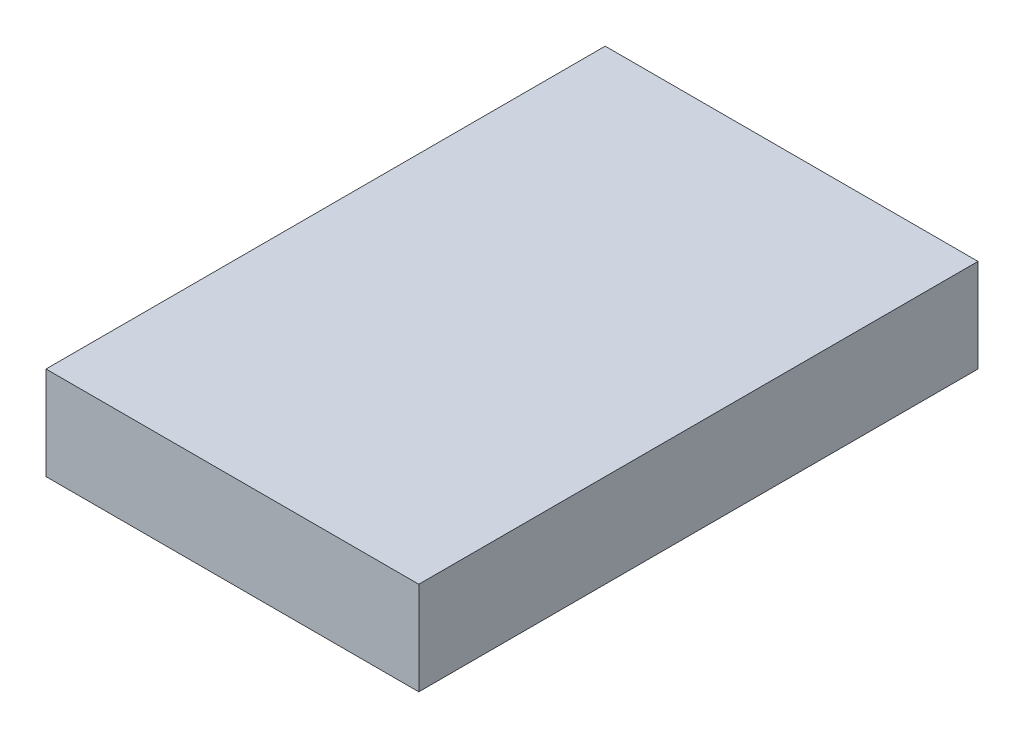
SolidWorks part; units mm, degrees
ref_plane "Front Plane" through (0, 0, 0) normal (0, 0, 1) x (1, 0, 0)
ref_plane "Top Plane" through (0, 0, 0) normal (0, 1, 0) x (1, 0, 0)
ref_plane "Right Plane" through (0, 0, 0) normal (1, 0, 0) x (0, 0, -1)
sketch "Sketch1" plane through (0, 0, 0) normal (0, 0, 1) x (1, 0, 0)
  line L1 (-20, 5) -> (20, 5)
  line L2 (-20, 5) -> (-20, -5)
  line L3 (-20, -5) -> (20, -5)
  line L4 (20, 5) -> (20, -5)
  line L5 (-20, 5) -> (20, -5) construction
  line L6 (-20, -5) -> (20, 5) construction
  point P0 (0, 0)
  dimension "D1" = 10
  dimension "D2" = 40
extrude "Boss-Extrude1" add sketch "Sketch1" along normal blind 60
ref_plane "Plane1" through (0, 0, 0) normal (0, 1, 0) x (1, 0, 0)
sketch "Sketch2" plane through (0, 0, 0) normal (0, 1, 0) x (1, 0, 0)
  line L1 (-20, -60) -> (20, -60) construction
  line L5 (0, -50) -> (0, -46)
  line L6 (1, -45) -> (15, -45)
  line L7 (15, -42) -> (0, -42)
  line L8 (0, -42) -> (-15, -42)
  line L9 (-15, -39) -> (15, -39)
  line L10 (15, -36) -> (-15, -36)
  line L11 (-15, -33) -> (15.3556, -33)
  line L12 (15.3556, -30) -> (-15, -30)
  line L13 (-15, -27) -> (15, -27)
  line L14 (15, -24) -> (-15, -24)
  line L15 (-15, -21) -> (15, -21)
  line L16 (15, -18) -> (-15, -18)
  line L17 (-15, -15) -> (15, -15)
  line L18 (15, -12) -> (1, -12)
  line L19 (0, -11) -> (0, -6)
  arc A0 (15, -45) -> (15, -42) centre (15, -43.5) ccw
  arc A1 (-15, -42) -> (-15, -39) centre (-15, -40.5) cw
  arc A2 (15, -39) -> (15, -36) centre (15, -37.5) ccw
  arc A3 (-15, -36) -> (-15, -33) centre (-15, -34.5) cw
  arc A4 (15.3556, -33) -> (15.3556, -30) centre (15.3556, -31.5) ccw
  arc A5 (-15, -30) -> (-15, -27) centre (-15, -28.5) cw
  arc A6 (15, -27) -> (15, -24) centre (15, -25.5) ccw
  arc A7 (-15, -24) -> (-15, -21) centre (-15, -22.5) cw
  arc A8 (15, -21) -> (15, -18) centre (15, -19.5) ccw
  arc A9 (-15, -18) -> (-15, -15) centre (-15, -16.5) cw
  arc A10 (15, -15) -> (15, -12) centre (15, -13.5) ccw
  arc A11 (0, -46) -> (1, -45) centre (1, -46) cw
  arc A12 (1, -12) -> (0, -11) centre (1, -11) cw
  point P5 (0, -45)
  point P9 (0, -12)
  dimension "D5" = 1
  dimension "D1" = 10
  dimension "D2" = 5
  dimension "D3" = 15
  dimension "D4" = 15
  dimension "D16" = 6
ref_plane "Plane2" through (0, 0, 6) normal (0, 0, -1) x (-1, 0, 0)
sketch "Sketch10" plane through (0, 0, 6) normal (0, 0, -1) x (-1, 0, 0)
  circle A0 centre (0, 0) radius 0.5
  dimension "D1" = 1
sketch "Sketch11" plane through (0, 0, 6) normal (0, 0, -1) x (-1, 0, 0)
sweep "Cut-Sweep1" cut profiles "Sketch10" path "Sketch2"
ref_plane "Plane4" through (0, 0, 0) normal (1, 0, 0) x (0, 0, -1)
ref_plane "Plane5" through (0, 0, 0) normal (0, 1, 0) x (1, 0, 0)
